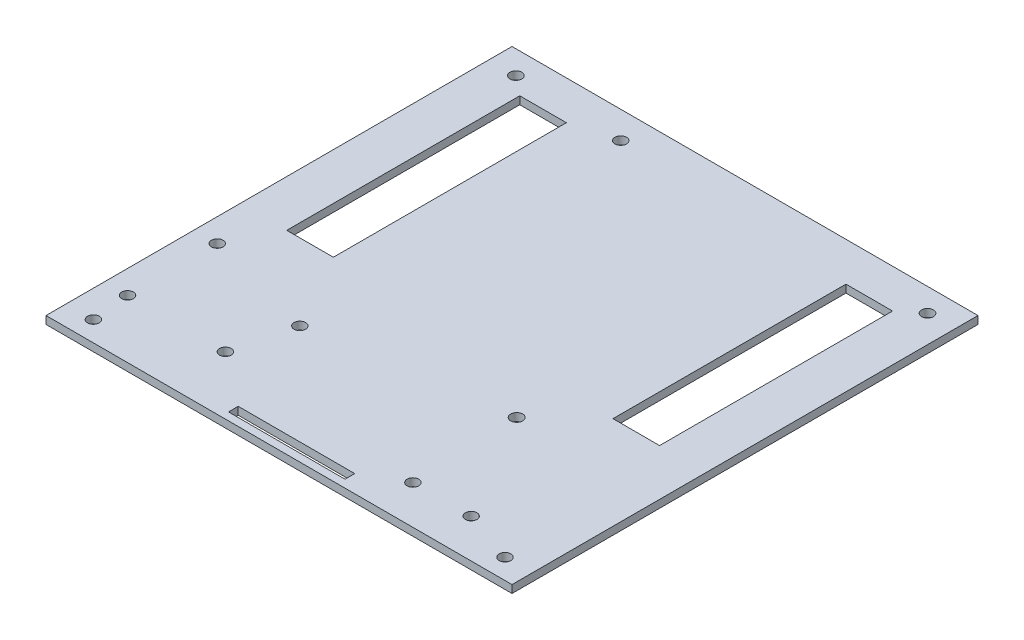
SolidWorks part; units mm, degrees
material "Perspex (TM) GS Acrylic Cast Sheet"
ref_plane "Front Plane" through (0, 0, 0) normal (0, 0, 1) x (1, 0, 0)
ref_plane "Top Plane" through (0, 0, 0) normal (0, 1, 0) x (1, 0, 0)
ref_plane "Right Plane" through (0, 0, 0) normal (1, 0, 0) x (0, 0, -1)
sketch "Sketch1" plane through (0, 0, 0) normal (0, 1, 0) x (1, 0, 0)
  line L1 (60, -60) -> (-60, -60)
  line L2 (60, -60) -> (60, 60)
  line L3 (60, 60) -> (-60, 60)
  line L4 (-60, -60) -> (-60, 60)
  line L5 (60, -60) -> (-60, 60) construction
  line L6 (60, 60) -> (-60, -60) construction
  point P0 (0, 0)
  dimension "D1" = 120
  dimension "D2" = 120
extrude "Boss-Extrude1" add sketch "Sketch1" along normal blind 2
sketch "Sketch2" plane through (0, 2, 0) normal (0, 1, 0) x (1, 0, 0)
  line L0 (0, 0) -> (0, 60) construction
  line L1 (60, 60) -> (-60, 60) construction
  line L2 (0, 0) -> (-60, 0) construction
  line L3 (-60, 60) -> (-60, -60) construction
  line L4 (-60, -60) -> (60, -60) construction
  circle A0 centre (-53, 54) radius 1.525
  circle A1 centre (-53, -54.8) radius 1.5
  circle A2 centre (53, 54) radius 1.525
  circle A3 centre (53, -54.8) radius 1.5
  dimension "D1" = 3.05
  dimension "D2" = 6
  dimension "D3" = 7
  dimension "D4" = 3
  dimension "D5" = 5.2
  dimension "D6" = 7
extrude "Cut-Extrude1" cut sketch "Sketch2" against normal blind 2
sketch "Sketch4" plane through (0, 2, 0) normal (0, 1, 0) x (1, 0, 0)
  line L0 (60, 60) -> (-60, 60) construction
  line L1 (-60, 60) -> (-60, -60) construction
  line L2 (0, 0) -> (0, 60) construction
  line L3 (-36, 50) -> (-48, 50)
  line L4 (-36, 50) -> (-36, -10)
  line L5 (-36, -10) -> (-48, -10)
  line L6 (-48, 50) -> (-48, -10)
  line L7 (-36, 50) -> (-48, -10) construction
  line L8 (-36, -10) -> (-48, 50) construction
  line L9 (36, -10) -> (48, -10)
  line L10 (36, 50) -> (36, -10)
  line L11 (48, 50) -> (48, -10)
  line L12 (36, 50) -> (48, 50)
  circle A0 centre (-25, 53) radius 1.5
  circle A1 centre (-25, -29.63) radius 1.5
  circle A2 centre (23.34, -22.13) radius 1.55
  point P10 (-42, 20)
  dimension "D1" = 3
  dimension "D2" = 3
  dimension "D4" = 7
  dimension "D5" = 35
  dimension "D6" = 35
  dimension "D7" = 3.1
  dimension "D8" = 48.34
  dimension "D3" = 82.63
  dimension "78" = 82.13
  dimension "D10" = 12
  dimension "D11" = 10
  dimension "D12" = 60
  dimension "D13" = 12
extrude "Cut-Extrude2" cut sketch "Sketch4" against normal through all
sketch "Sketch5" plane through (0, 2, 0) normal (0, 1, 0) x (1, 0, 0)
  line L0 (-60, 60) -> (-60, -60) construction
  line L1 (-60, -60) -> (60, -60) construction
  line L3 (15, -58) -> (-15, -58)
  line L4 (15, -58) -> (15, -55.5)
  line L5 (15, -55.5) -> (-15, -55.5)
  line L6 (-15, -58) -> (-15, -55.5)
  line L7 (15, -58) -> (-15, -55.5) construction
  line L8 (15, -55.5) -> (-15, -58) construction
  circle A0 centre (-54, -45) radius 1.5
  circle A1 centre (-28.82, -45) radius 1.5
  circle A2 centre (-54, -21.9) radius 1.5
  circle A3 centre (24.4796, -50) radius 1.5
  circle A4 centre (39.4796, -50) radius 1.5
  point P10 (0, -56.75)
  point P20 (39.1836, -63.3826)
  point P21 (24.1836, -63.3826)
  point P22 (24.1836, -63.3826)
  point P23 (0, 0)
  point P24 (24.4796, -49.8197)
  dimension "D1" = 3
  dimension "D2" = 3
  dimension "D4" = 3
  dimension "D8" = 15
  dimension "D9" = 15
  dimension "D15" = 3
  dimension "D3" = 25.18
  dimension "D5" = 23.1
  dimension "D6" = 6
  dimension "D7" = 6
  dimension "D10" = 2
  dimension "D11" = 2.5
  dimension "D12" = 30
  dimension "D13" = 10
  dimension "D14" = 15
extrude "Cut-Extrude3" cut sketch "Sketch5" against normal through all
